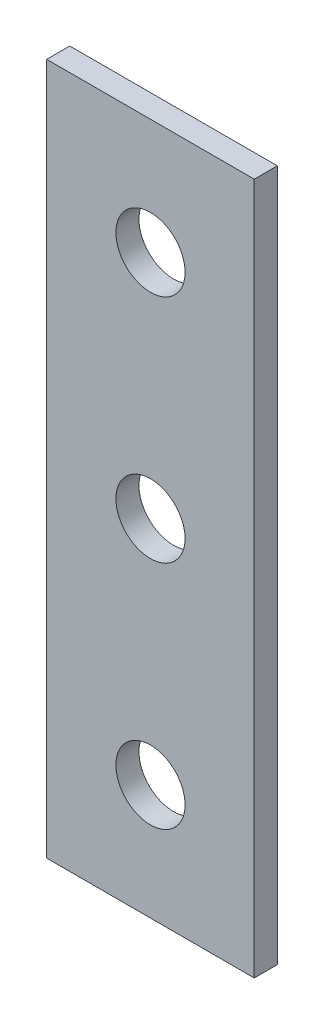
SolidWorks part; units mm, degrees
ref_plane "Alzado" through (0, 0, 0) normal (0, 0, 1) x (1, 0, 0)
ref_plane "Planta" through (0, 0, 0) normal (0, 1, 0) x (1, 0, 0)
ref_plane "Vista lateral" through (0, 0, 0) normal (1, 0, 0) x (0, 0, -1)
sketch "Croquis1" plane through (0, 0, 0) normal (0, 0, 1) x (1, 0, 0)
  line L0 (0, 0) -> (0, 30)
  line L1 (0, 30) -> (9, 30)
  line L2 (9, 30) -> (9, 0)
  line L3 (9, 0) -> (0, 0)
  circle A0 centre (4.5, 25) radius 1.5
  circle A1 centre (4.5, 15) radius 1.5
  circle A2 centre (4.5, 5) radius 1.5
extrude "Saliente-Extruir1" add sketch "Croquis1" along normal blind 1
